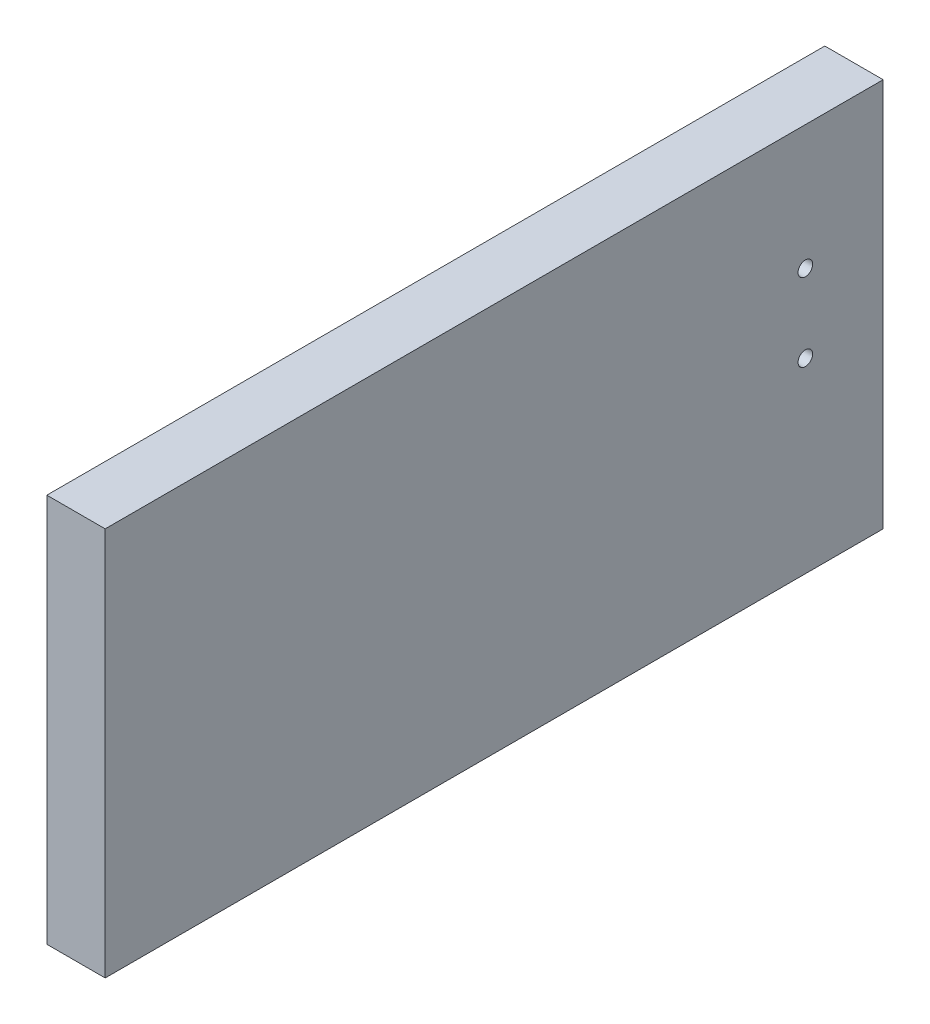
SolidWorks part; units mm, degrees
ref_plane "Front Plane" through (0, 0, 0) normal (0, 0, 1) x (1, 0, 0)
ref_plane "Top Plane" through (0, 0, 0) normal (0, 1, 0) x (1, 0, 0)
ref_plane "Right Plane" through (0, 0, 0) normal (1, 0, 0) x (0, 0, -1)
sketch "Sketch1" plane through (0, 0, 0) normal (0, 0, 1) x (1, 0, 0)
  line L1 (-9.525, 63.5) -> (9.525, 63.5)
  line L2 (-9.525, 63.5) -> (-9.525, -63.5)
  line L3 (-9.525, -63.5) -> (9.525, -63.5)
  line L4 (9.525, 63.5) -> (9.525, -63.5)
  line L5 (-9.525, 63.5) -> (9.525, -63.5) construction
  line L6 (-9.525, -63.5) -> (9.525, 63.5) construction
  point P0 (0, 0)
  dimension "D1" = 127
  dimension "D2" = 19.05
extrude "Boss-Extrude1" add sketch "Sketch1" along normal blind 254
sketch "Sketch2" plane through (-9.525, 0, 0) normal (-1, 0, 0) x (0, 0, 1)
  circle A0 centre (25.4, 22.86) radius 2.3813
  circle A1 centre (25.4, -2.54) radius 2.3813
extrude "Cut-Extrude1" cut sketch "Sketch2" against normal through all
